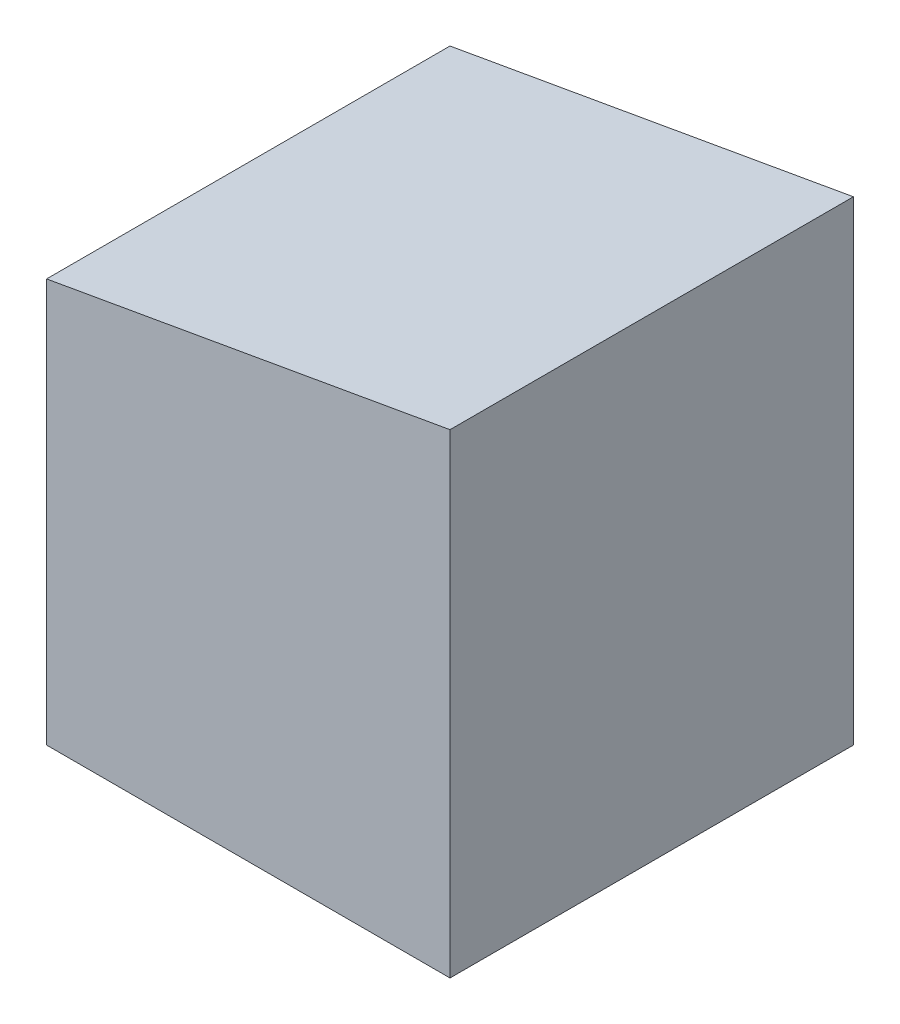
SolidWorks part; units mm, degrees
material "Oak"
ref_plane "Front Plane" through (0, 0, 0) normal (0, 0, 1) x (1, 0, 0)
ref_plane "Top Plane" through (0, 0, 0) normal (0, 1, 0) x (1, 0, 0)
ref_plane "Right Plane" through (0, 0, 0) normal (1, 0, 0) x (0, 0, -1)
sketch "Sketch1" plane through (0, 0, 0) normal (0, 1, 0) x (1, 0, 0)
  line L1 (-44.45, -44.45) -> (44.45, -44.45)
  line L2 (-44.45, -44.45) -> (-44.45, 44.45)
  line L3 (-44.45, 44.45) -> (44.45, 44.45)
  line L4 (44.45, -44.45) -> (44.45, 44.45)
  line L5 (-44.45, -44.45) -> (44.45, 44.45) construction
  line L6 (-44.45, 44.45) -> (44.45, -44.45) construction
  point P0 (0, 0)
  dimension "D1" = 88.9
  dimension "D2" = 88.9
extrude "Boss-Extrude1" add sketch "Sketch1" along normal blind 104.648
sketch "Sketch2" plane through (0, 0, 44.45) normal (0, 0, 1) x (1, 0, 0)
  line L0 (44.45, 104.648) -> (-44.45, 88.9725)
  line L1 (-44.45, 104.648) -> (-44.45, 0) construction
  line L2 (-44.45, 88.9725) -> (-44.45, 104.648)
  line L3 (-44.45, 104.648) -> (44.45, 104.648)
  dimension "D1" = 10
extrude "Cut-Extrude1" cut sketch "Sketch2" against normal blind 135
